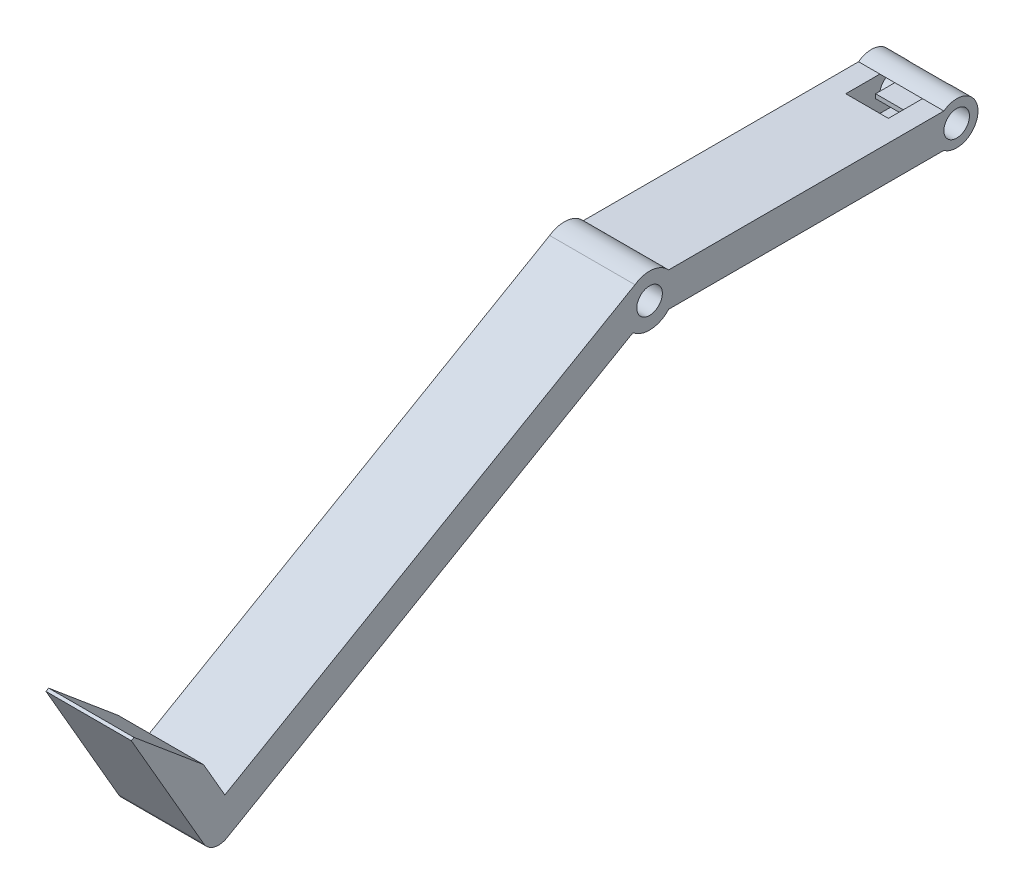
SolidWorks part; units mm, degrees
ref_plane "Front Plane" through (0, 0, 0) normal (0, 0, 1) x (1, 0, 0)
ref_plane "Top Plane" through (0, 0, 0) normal (0, 1, 0) x (1, 0, 0)
ref_plane "Right Plane" through (0, 0, 0) normal (1, 0, 0) x (0, 0, -1)
sketch "Sketch1" plane through (0, 0, 0) normal (0, 1, 0) x (1, 0, 0)
  line L1 (-5, 18) -> (5, 18)
  line L2 (-5, 18) -> (-5, -18)
  line L3 (-5, -18) -> (5, -18)
  line L4 (5, 18) -> (5, -18)
  line L5 (-5, 18) -> (5, -18) construction
  line L6 (-5, -18) -> (5, 18) construction
  point P0 (0, 0)
  dimension "D1" = 10
  dimension "D2" = 36
extrude "Boss-Extrude2" add sketch "Sketch1" along normal blind 4
sketch "Sketch5" plane through (5, 0, 0) normal (1, 0, 0) x (0, 0, -1)
  line L0 (-18, 4) -> (-18, 0) construction
  circle A0 centre (-18, 2) radius 3
  dimension "D1" = 6
extrude "Boss-Extrude3" add sketch "Sketch5" against normal blind 10 contours A0
sketch "Sketch6" plane through (5, 0, 0) normal (1, 0, 0) x (0, 0, -1)
  line L0 (18, 4) -> (18, 0) construction
  circle A0 centre (18, 2) radius 2.5
  dimension "D1" = 5
extrude "Boss-Extrude4" add sketch "Sketch6" against normal blind 10
sketch "Sketch7" plane through (5, 0, 0) normal (1, 0, 0) x (0, 0, -1)
  circle A0 centre (-18, 2) radius 1.5
  dimension "D1" = 3
sketch "Sketch9" plane through (5, 0, 0) normal (1, 0, 0) x (0, 0, -1)
  circle A0 centre (18, 2) radius 1.5
  dimension "D1" = 3
extrude "Cut-Extrude2" cut sketch "Sketch9" against normal blind 10
sketch "Sketch10" plane through (0, 4, 0) normal (0, 1, 0) x (1, 0, 0)
  line L0 (-5, 16.5) -> (5, 16.5) construction
  line L1 (-2.5, 12.5) -> (2.5, 12.5)
  line L2 (-2.5, 12.5) -> (-2.5, 20.5)
  line L3 (-2.5, 20.5) -> (2.5, 20.5)
  line L4 (2.5, 12.5) -> (2.5, 20.5)
  line L5 (-2.5, 12.5) -> (2.5, 20.5) construction
  line L6 (-2.5, 20.5) -> (2.5, 12.5) construction
  point P0 (0, 16.5)
  dimension "D1" = 5
  dimension "D2" = 8
extrude "Cut-Extrude3" cut sketch "Sketch10" against normal blind 4
sketch "Sketch11" plane through (2.5, 0, 0) normal (-1, 0, 0) x (0, 0, 1)
  line L1 (-16, 2.25) -> (-20, 2.25)
  line L2 (-16, 2.25) -> (-16, 1.75)
  line L3 (-16, 1.75) -> (-20, 1.75)
  line L4 (-20, 2.25) -> (-20, 1.75)
  line L5 (-16, 2.25) -> (-20, 1.75) construction
  line L6 (-16, 1.75) -> (-20, 2.25) construction
  point P0 (-18, 2)
  dimension "D1" = 4
  dimension "D2" = 0.5
extrude "Boss-Extrude6" add sketch "Sketch11" along normal blind 5
sketch "Sketch13" plane through (5, 0, 0) normal (1, 0, 0) x (0, 0, -1)
  line L0 (-19.283, 4.7118) -> (-71.2445, -25.2882)
  line L1 (-19.283, 4.7118) -> (-17.283, 1.2477)
  line L2 (-71.2445, -25.2882) -> (-69.2445, -28.7523)
  line L3 (-17.283, 1.2477) -> (-69.2445, -28.7523)
  line L5 (-15.7639, 0) -> (16.5, 0) construction
  arc A0 (-15.7639, 4) -> (-15.7639, 0) centre (-18, 2) ccw construction
  dimension "D1" = 150
  dimension "D2" = 4
  dimension "D3" = 60
  dimension "D4" = 90
extrude "Boss-Extrude7" add sketch "Sketch13" against normal blind 10
extrude "Cut-Extrude4" cut sketch "Sketch7" against normal blind 10
sketch "Sketch14" plane through (0, 11.8836, 6.861) normal (0, 0.866, 0.5) x (1, 0, 0)
  line L0 (-5, -14.8333) -> (-5, -74.3436) construction
  line L1 (5, -74.3436) -> (-5, -74.3436)
  line L2 (5, -74.3436) -> (5, -70.3436)
  line L3 (5, -70.3436) -> (-5, -70.3436)
  line L4 (-5, -74.3436) -> (-5, -70.3436)
  dimension "D1" = 4
extrude "Boss-Extrude8" add sketch "Sketch14" along normal blind 15
fillet "Fillet2" radius 2 1 edges at (0, -28.7523, 69.2445)
chamfer "Chamfer1" distance 10 angle 20 1 edges at (0, -10.2978, 75.2804)
